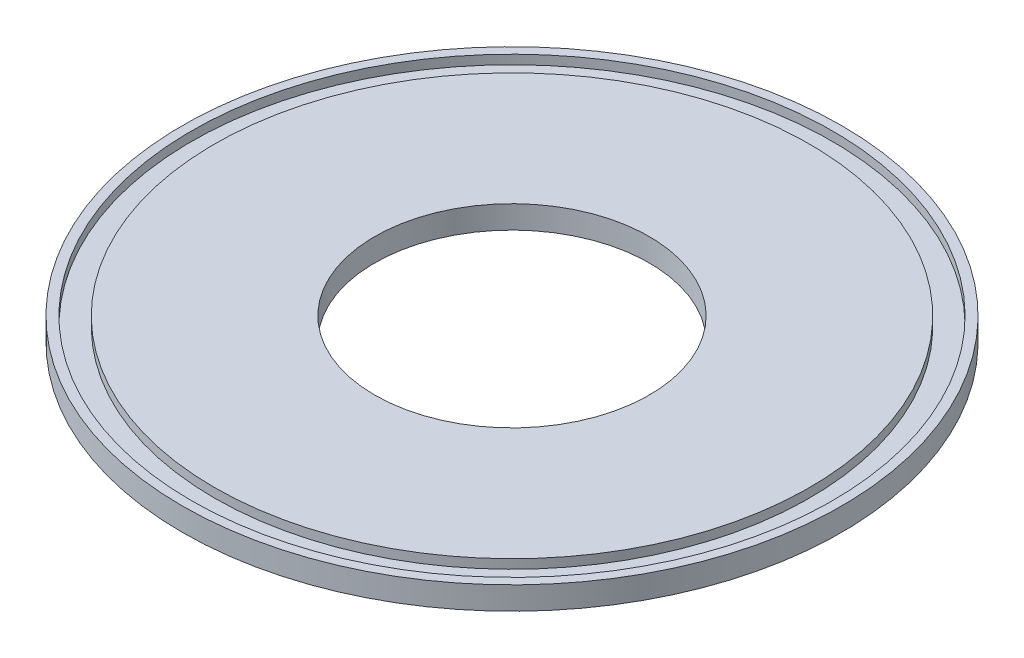
SolidWorks part; units mm, degrees
ref_plane "Front Plane" through (0, 0, 0) normal (0, 0, 1) x (1, 0, 0)
ref_plane "Top Plane" through (0, 0, 0) normal (0, 1, 0) x (1, 0, 0)
ref_plane "Right Plane" through (0, 0, 0) normal (1, 0, 0) x (0, 0, -1)
sketch "Sketch1" plane through (0, 0, 0) normal (0, 1, 0) x (1, 0, 0)
  line L0 (0, 67.5482) -> (0, -50.0189) construction
  circle A0 centre (0, 0) radius 360
  circle A1 centre (0, 0) radius 150
  dimension "D1" = 720
  dimension "D2" = 300
extrude "Boss-Extrude1" add sketch "Sketch1" along normal mid plane 25
sketch "Sketch2" plane through (0, 12.5, 0) normal (0, 1, 0) x (1, 0, 0)
  circle A0 centre (0, 0) radius 350
  circle A1 centre (0, 0) radius 325
  dimension "D1" = 700
  dimension "D2" = 650
extrude "Cut-Extrude1" cut sketch "Sketch2" against normal blind 10
